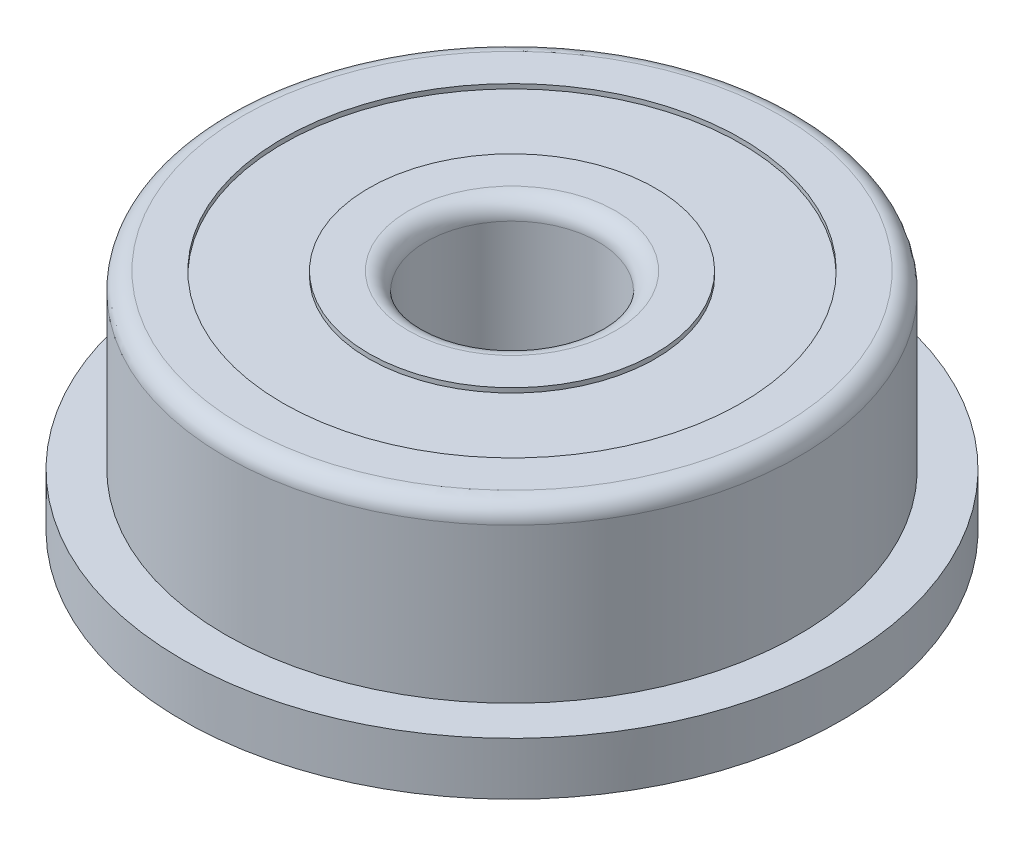
SolidWorks part; units mm, degrees
ref_plane "Front Plane" through (0, 0, 0) normal (0, 0, 1) x (1, 0, 0)
ref_plane "Top Plane" through (0, 0, 0) normal (0, 1, 0) x (1, 0, 0)
ref_plane "Right Plane" through (0, 0, 0) normal (1, 0, 0) x (0, 0, -1)
sketch "Sketch1" plane through (0, 0, 0) normal (0, 1, 0) x (1, 0, 0)
  circle A0 centre (0, 0) radius 5.75
  dimension "D1" = 11.5
extrude "Boss-Extrude1" add sketch "Sketch1" along normal blind 1
sketch "Sketch2" plane through (0, 1, 0) normal (0, 1, 0) x (1, 0, 0)
  circle A0 centre (0, 0) radius 5
  dimension "D1" = 10
extrude "Boss-Extrude2" add sketch "Sketch2" along normal blind 3
sketch "Sketch3" plane through (0, 4, 0) normal (0, 1, 0) x (1, 0, 0)
  circle A0 centre (0, 0) radius 1.5
  dimension "D1" = 3
extrude "Cut-Extrude1" cut sketch "Sketch3" against normal through all
sketch "Sketch4" plane through (0, 0, 0) normal (0, -1, 0) x (1, 0, 0)
  circle A0 centre (0, 0) radius 762
  circle A1 centre (0, 0) radius 4
  dimension "D1" = 8
  dimension "D2" = 1524
extrude "Cut-Extrude2" cut sketch "Sketch4" against normal blind 0.08
sketch "Sketch5" plane through (0, 4, 0) normal (0, 1, 0) x (1, 0, 0)
  circle A0 centre (0, 0) radius 2.5
  circle A1 centre (0, 0) radius 4
  dimension "D1" = 8
  dimension "D2" = 5
extrude "Cut-Extrude3" cut sketch "Sketch5" against normal blind 0.08
fillet "Fillet1" radius 0.31 3 edges at (0, 0, 1.5) (0, 4, 5) (0, 4, 1.5)
